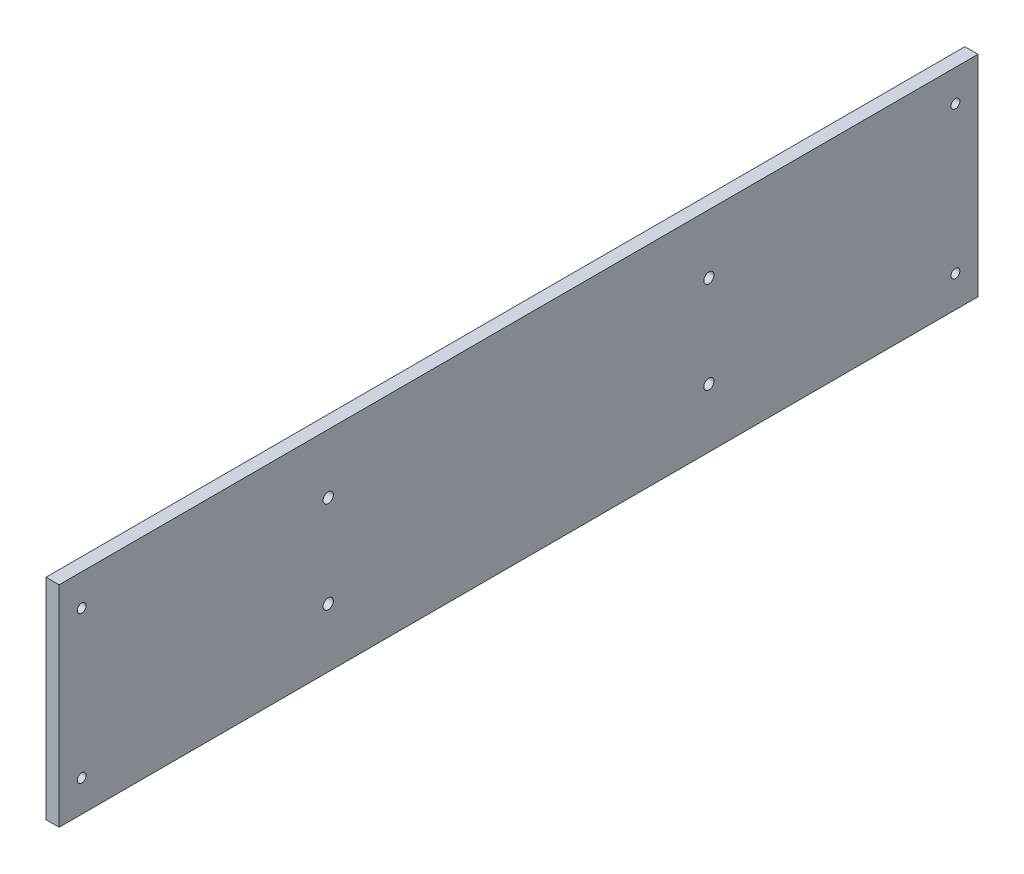
SolidWorks part; units mm, degrees
material "6061-T6 (SS)"
ref_plane "Front Plane" through (0, 0, 0) normal (0, 0, 1) x (1, 0, 0)
ref_plane "Top Plane" through (0, 0, 0) normal (0, 1, 0) x (1, 0, 0)
ref_plane "Right Plane" through (0, 0, 0) normal (1, 0, 0) x (0, 0, -1)
sketch "Sketch1" plane through (0, 0, 0) normal (1, 0, 0) x (0, 0, -1)
  line L1 (-222.25, 50.8) -> (222.25, 50.8)
  line L2 (-222.25, 50.8) -> (-222.25, -50.8)
  line L3 (-222.25, -50.8) -> (222.25, -50.8)
  line L4 (222.25, 50.8) -> (222.25, -50.8)
  line L5 (-222.25, 50.8) -> (222.25, -50.8) construction
  line L6 (-222.25, -50.8) -> (222.25, 50.8) construction
  point P0 (0, 0)
  dimension "D1" = 101.6
  dimension "D2" = 444.5
extrude "Boss-Extrude1" add sketch "Sketch1" along normal blind 6.35
sketch "Sketch2" plane through (6.35, 0, 0) normal (1, 0, 0) x (0, 0, -1)
  line L0 (222.25, -50.8) -> (222.25, 50.8) construction
  line L1 (-188.722, 10.16) -> (211.328, 10.16) construction
  line L2 (-188.722, 10.16) -> (-188.722, -44.45) construction
  line L3 (-188.722, -44.45) -> (211.328, -44.45) construction
  line L4 (211.328, 10.16) -> (211.328, -44.45) construction
  line L5 (-188.722, 10.16) -> (211.328, -44.45) construction
  line L6 (-188.722, -44.45) -> (211.328, 10.16) construction
  line L7 (-222.25, 50.8) -> (-222.25, -50.8) construction
  line L8 (-222.25, -50.8) -> (222.25, -50.8) construction
  line L9 (-222.25, -50.8) -> (222.25, -50.8) construction
  line L10 (222.25, -50.8) -> (222.25, 50.8) construction
  line L11 (130.175, 3.81) -> (47.625, 3.81) construction
  line L12 (130.175, 3.81) -> (130.175, -40.64) construction
  line L13 (130.175, -40.64) -> (47.625, -40.64) construction
  line L14 (47.625, 3.81) -> (47.625, -40.64) construction
  line L15 (130.175, 3.81) -> (47.625, -40.64) construction
  line L16 (130.175, -40.64) -> (47.625, 3.81) construction
  line L17 (-217.4875, 46.9519) -> (-217.4875, 38.7731) construction
  line L18 (-222.25, 50.8) -> (-222.25, -50.8) construction
  line L19 (222.25, 50.8) -> (-222.25, 50.8) construction
  point P0 (11.303, -17.145)
  point P7 (0, 0)
  point P8 (-208.534, -15.24)
  point P14 (-217.4875, 42.8625)
  point P18 (88.9, -18.415)
  dimension "D1" = 10.922
  dimension "D2" = 33.528
  dimension "D3" = 54.61
  dimension "D4" = 13.716
  dimension "D5" = 35.56
  dimension "D6" = 6.35
  dimension "D7" = 82.55
  dimension "D8" = 44.45
  dimension "D9" = 10.16
  dimension "D10" = 92.075
  dimension "D11" = 8.1788
  dimension "D12" = 4.7625
  dimension "D13" = 7.9375
hole_wizard "#10 Clearance Hole1" positions "Sketch3" profile "Sketch4" hole size "#10" standard "ANSI Inch" end condition through all
sketch "Sketch3" plane through (6.35, 0, 0) normal (1, 0, 0) x (0, 0, -1)
  line L0 (222.25, 50.8) -> (-222.25, 50.8) construction
  line L1 (222.25, -50.8) -> (222.25, 50.8) construction
  line L2 (-222.25, 50.8) -> (-222.25, -50.8) construction
  point P28 (92.075, 22.225)
  point P30 (92.075, -22.225)
  point P35 (-92.075, 22.225)
  point P37 (-92.075, -22.225)
  dimension "D1" = 28.575
  dimension "D2" = 73.025
  dimension "D3" = 28.575
  dimension "D4" = 73.025
  dimension "D5" = 130.175
  dimension "D6" = 130.175
  dimension "D7" = 130.175
  dimension "D8" = 130.175
sketch "Sketch4" plane through (6.35, 22.225, -92.075) normal (0, 1, 0) x (0, 0, -1)
  line L0 (0, 0) -> (0, 6.35)
  line L1 (0, 6.35) -> (2.4892, 6.35)
  line L2 (2.4892, 6.35) -> (2.4892, 0)
  line L5 (2.4892, 0) -> (0, 0)
  line L11 (0, -6.35) -> (0, 107.95) construction
  dimension "Thru Hole Dia." = 4.9784
  dimension "Thru Hole Depth" = 6.35
hole_wizard "#8 Clearance Hole1" positions "Sketch7" profile "Sketch8" hole size "#8" standard "ANSI Inch" end condition through all
sketch "Sketch7" plane through (6.35, 0, 0) normal (1, 0, 0) x (0, 0, -1)
  line L0 (-222.25, 50.8) -> (-222.25, -50.8) construction
  line L1 (222.25, 50.8) -> (-222.25, 50.8) construction
  line L2 (222.25, -50.8) -> (222.25, 50.8) construction
  point P24 (-211.328, 35.56)
  point P26 (-211.328, -35.56)
  point P28 (211.328, -35.56)
  point P30 (211.328, 35.56)
  point P39 (0, 0)
  point P40 (0, 0)
  point P41 (0, 0)
  point P42 (0, 0)
  dimension "D1" = 10.922
  dimension "D2" = 10.922
  dimension "D3" = 15.24
  dimension "D4" = 86.36
  dimension "D5" = 10.922
  dimension "D6" = 10.922
  dimension "D7" = 86.36
  dimension "D8" = 15.24
sketch "Sketch8" plane through (6.35, 35.56, 211.328) normal (0, 1, 0) x (0, 0, -1)
  line L0 (0, 0) -> (0, 6.35)
  line L1 (0, 6.35) -> (2.1526, 6.35)
  line L2 (2.1526, 6.35) -> (2.1526, 0)
  line L5 (2.1526, 0) -> (0, 0)
  line L11 (0, -6.35) -> (0, 107.95) construction
  dimension "Thru Hole Dia." = 4.3053
  dimension "Thru Hole Depth" = 6.35
sketch "Sketch9" plane through (6.35, 0, 0) normal (1, 0, 0) x (0, 0, -1)
  line L12 (217.424, -45.974) -> (217.424, 45.974)
  line L13 (217.424, 45.974) -> (-217.424, 45.974)
  line L14 (-217.424, -45.974) -> (217.424, -45.974)
  line L15 (-217.424, 45.974) -> (-217.424, -45.974)
  line L16 (217.424, -45.974) -> (217.424, 45.974)
  line L17 (217.424, 45.974) -> (-217.424, 45.974)
  line L18 (-217.424, -45.974) -> (217.424, -45.974)
  line L19 (-217.424, 45.974) -> (-217.424, -45.974)
  circle A9 centre (-211.328, 35.56) radius 6.35
  circle A10 centre (-211.328, -35.56) radius 6.35
  circle A11 centre (-92.075, 22.225) radius 6.35
  circle A12 centre (-92.075, -22.225) radius 6.35
  circle A13 centre (92.075, 22.225) radius 6.35
  circle A14 centre (92.075, -22.225) radius 6.35
  circle A15 centre (211.328, 35.56) radius 6.35
  circle A16 centre (211.328, -35.56) radius 6.35
  dimension "D3" = 4.826
extrude "Cut-Extrude1" [suppressed] cut sketch "Sketch9" against normal through all
sketch "Sketch11" [suppressed] plane through (0, 0, 0) normal (-1, 0, 0) x (0, 0, 1)
  line L0 (-217.424, -29.972) -> (-217.424, 21.082) construction
  line L1 (-134.8644, -33.274) -> (-205.1636, -33.274) construction
  text T0 "LORD OF THE RINKS" font "Agency FB" height 45.72
  dimension "D1" = 4.064
  dimension "D2" = 10.668
extrude "Boss-Extrude3" [suppressed] add sketch "Sketch11" against normal up to surface (6.35 mm away)
